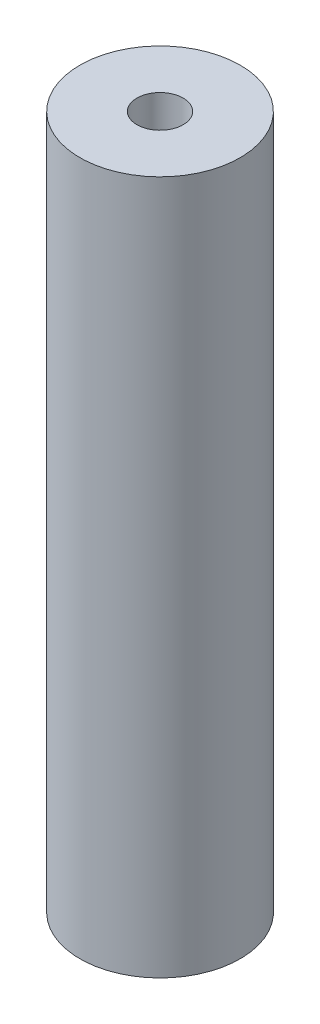
SolidWorks part; units mm, degrees
material "ABS"
ref_plane "Спереди" through (0, 0, 0) normal (0, 0, 1) x (1, 0, 0)
ref_plane "Сверху" through (0, 0, 0) normal (0, 1, 0) x (1, 0, 0)
ref_plane "Справа" through (0, 0, 0) normal (1, 0, 0) x (0, 0, -1)
sketch "Эскиз1" plane through (0, 0, 0) normal (0, 1, 0) x (1, 0, 0)
  circle A0 centre (0, 0) radius 3.2
  circle A1 centre (0, 0) radius 5.2
  dimension "D1" = 2
extrude "Бобышка-Вытянуть1" add sketch "Эскиз1" along normal blind 45
sketch "Эскиз2" plane through (0, 45, 0) normal (0, 1, 0) x (1, 0, 0)
  circle A0 centre (0, 0) radius 5.2
  circle A1 centre (0, 0) radius 1.5
extrude "Бобышка-Вытянуть2" add sketch "Эскиз2" against normal blind 4
sketch "Эскиз3" plane through (0, 0, 0) normal (0, -1, 0) x (1, 0, 0)
  circle A0 centre (0, 0) radius 5.2
  circle A1 centre (0, 0) radius 1.5
extrude "Бобышка-Вытянуть3" add sketch "Эскиз3" against normal blind 4
